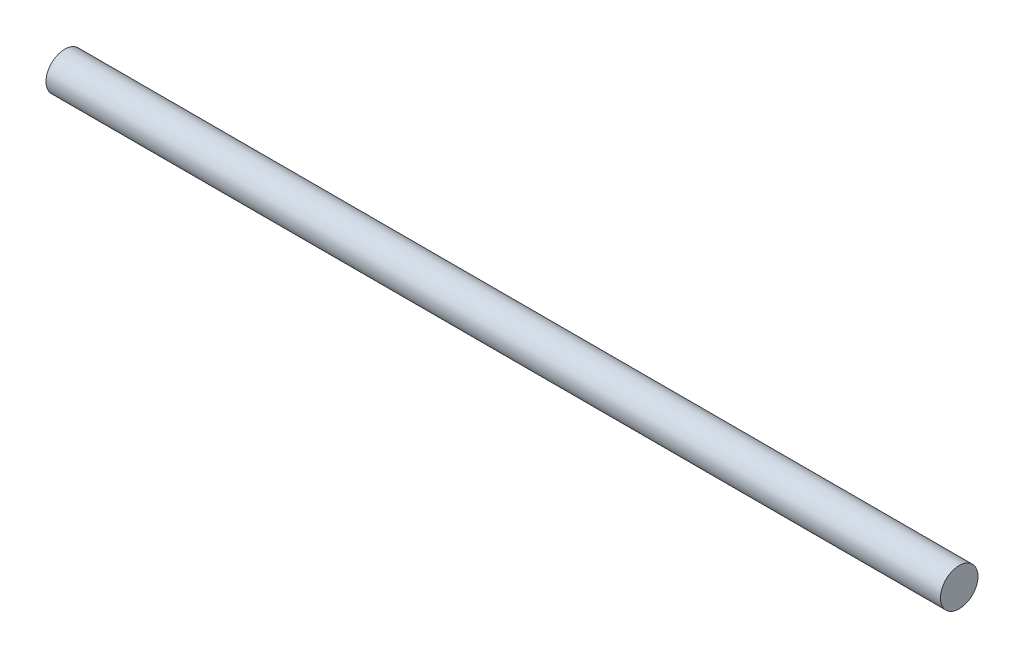
SolidWorks part; units mm, degrees
ref_plane "Front Plane" through (0, 0, 0) normal (0, 0, 1) x (1, 0, 0)
ref_plane "Top Plane" through (0, 0, 0) normal (0, 1, 0) x (1, 0, 0)
ref_plane "Right Plane" through (0, 0, 0) normal (1, 0, 0) x (0, 0, -1)
sketch "Sketch1" plane through (0, 0, 0) normal (1, 0, 0) x (0, 0, -1)
  circle A0 centre (0, 0) radius 10
  dimension "D1" = 20
extrude "Boss-Extrude1" add sketch "Sketch1" along normal blind 590
sketch "Sketch2" plane through (0, 0, 0) normal (-1, 0, 0) x (0, 0, 1)
  circle A0 centre (0, 0) radius 114
extrude "Cut-Extrude1" cut sketch "Sketch2" against normal blind 114
